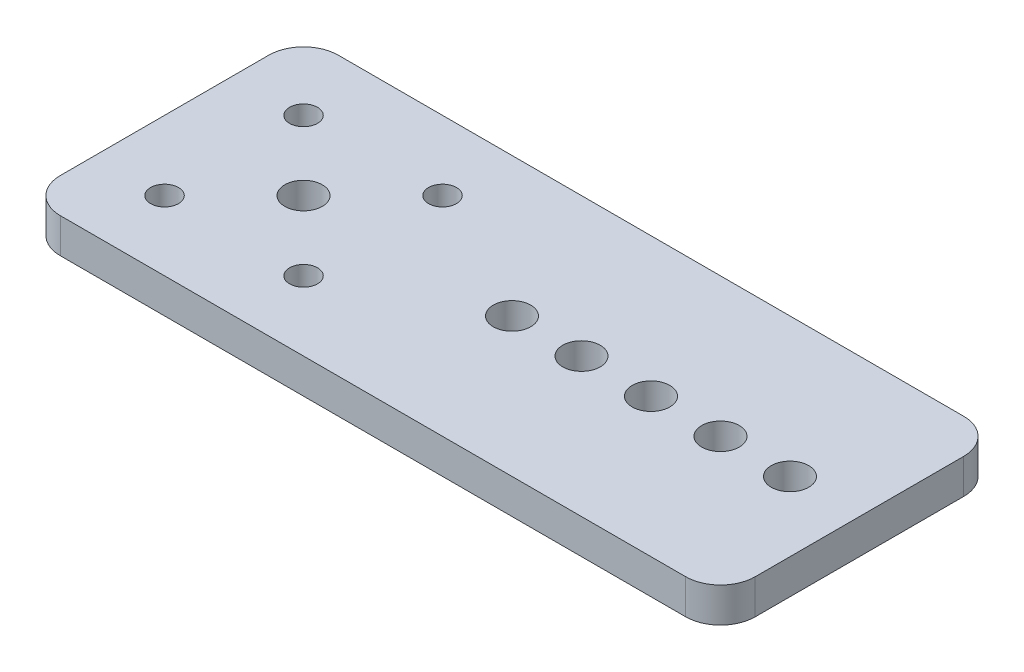
SolidWorks part; units mm, degrees
ref_plane "Front Plane" through (0, 0, 0) normal (0, 0, 1) x (1, 0, 0)
ref_plane "Top Plane" through (0, 0, 0) normal (0, 1, 0) x (1, 0, 0)
ref_plane "Right Plane" through (0, 0, 0) normal (1, 0, 0) x (0, 0, -1)
sketch "Sketch1" plane through (0, 0, 0) normal (0, 1, 0) x (1, 0, 0)
  line L5 (0, 0) -> (127, 0)
  line L6 (0, 0) -> (0, -50.8)
  line L7 (0, -50.8) -> (127, -50.8)
  line L8 (127, 0) -> (127, -50.8)
  circle A1 centre (12.7, -12.7) radius 2.5527
  circle A2 centre (38.1, -12.7) radius 2.5527
  circle A3 centre (38.1, -38.1) radius 2.5527
  circle A4 centre (12.7, -38.1) radius 2.5527
  circle A5 centre (25.4, -25.4) radius 3.429
  circle A8 centre (63.5, -25.4) radius 3.429
  circle A9 centre (76.2, -25.4) radius 3.429
  circle A10 centre (88.9, -25.4) radius 3.429
  circle A11 centre (101.6, -25.4) radius 3.429
  circle A12 centre (114.3, -25.4) radius 3.429
  circle A13 centre (38.1, -25.4) radius 3.429 [skipped]
  circle A14 centre (50.8, -25.4) radius 3.429 [skipped]
  dimension "D1" = 50.8
  dimension "D3" = 5.1054
  dimension "D8" = 6.858
  dimension "D2" = 127
  dimension "D4" = 12.7
  dimension "D5" = 12.7
  dimension "D9" = 25.4
  dimension "D10" = 25.4
  dimension "D6" = 2
  dimension "D7" = 2
  dimension "D11" = 8
extrude "Boss-Extrude1" add sketch "Sketch1" along normal blind 6.35
fillet "Fillet1" radius 6.35 4 edges at (0, 3.175, 0) (0, 3.175, 50.8) (127, 3.175, 0) (127, 3.175, 50.8)
